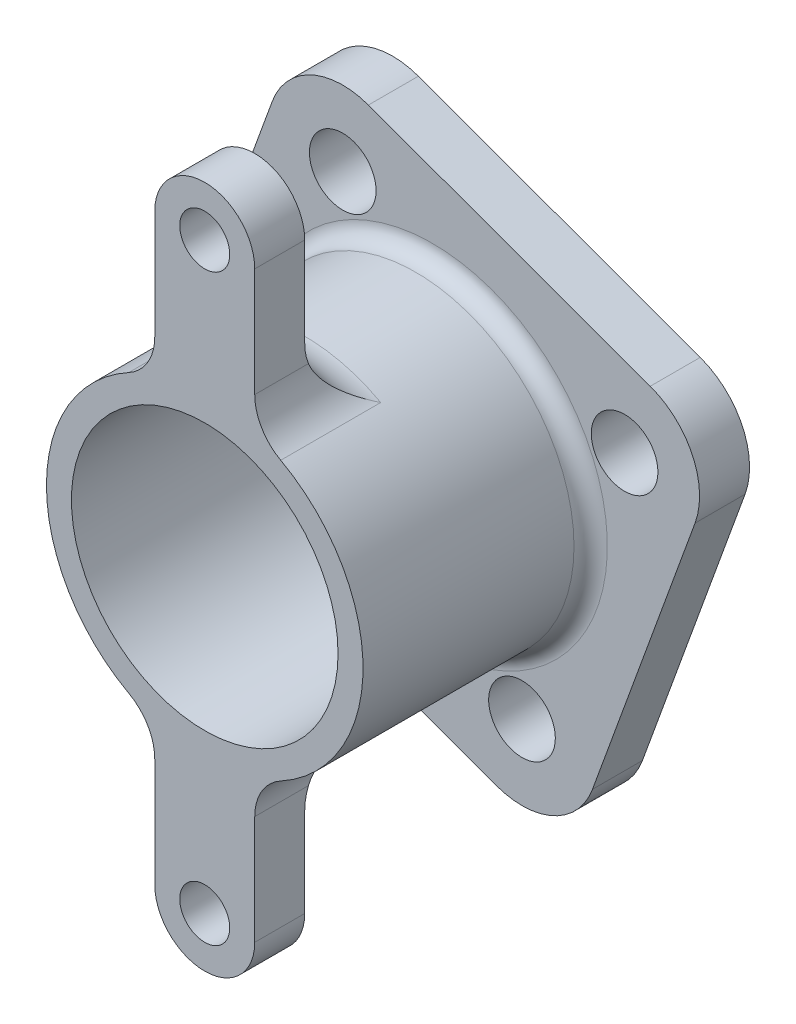
SolidWorks part; units mm, degrees
material "ABS"
ref_plane "Front Plane" through (0, 0, 0) normal (0, 0, 1) x (1, 0, 0)
ref_plane "Top Plane" through (0, 0, 0) normal (0, 1, 0) x (1, 0, 0)
ref_plane "Right Plane" through (0, 0, 0) normal (1, 0, 0) x (0, 0, -1)
sketch "Sketch1" plane through (0, 0, 0) normal (0, 0, 1) x (1, 0, 0)
  line L1 (-20.0745, -9.6077) -> (-3.16, -15.764)
  line L2 (-22.764, -3.84) -> (-16.6077, 13.0745)
  line L3 (-10.84, 15.764) -> (6.0745, 9.6077)
  line L4 (2.6077, -13.0745) -> (8.764, 3.84)
  line L5 (-24.3031, -8.0686) -> (10.3031, 8.0686) construction
  line L6 (-15.0686, 17.3031) -> (1.0686, -17.3031) construction
  line L7 (-18.5354, -5.3791) -> (-1.6209, -11.5354) construction
  line L12 (-18.5354, -5.3791) -> (-12.3791, 11.5354) construction
  line L13 (-12.3791, 11.5354) -> (4.5354, 5.3791) construction
  line L14 (-1.6209, -11.5354) -> (4.5354, 5.3791) construction
  line L15 (-18.5354, -5.3791) -> (4.5354, 5.3791) construction
  line L16 (-12.3791, 11.5354) -> (-1.6209, -11.5354) construction
  arc A4 (6.0745, 9.6077) -> (8.764, 3.84) centre (4.5354, 5.3791) cw
  arc A5 (-3.16, -15.764) -> (2.6077, -13.0745) centre (-1.6209, -11.5354) ccw
  arc A6 (-20.0745, -9.6077) -> (-22.764, -3.84) centre (-18.5354, -5.3791) cw
  arc A7 (-16.6077, 13.0745) -> (-10.84, 15.764) centre (-12.3791, 11.5354) cw
  circle A16 centre (-7, 0) radius 8
  circle A17 centre (-12.3791, 11.5354) radius 2
  circle A18 centre (4.5354, 5.3791) radius 2
  circle A19 centre (-1.6209, -11.5354) radius 2
  circle A20 centre (-18.5354, -5.3791) radius 2
  dimension "D2" = 16
  dimension "D4" = 4.5
  dimension "D6" = 4
  dimension "D1" = 27
  dimension "D3" = 27
  dimension "D5" = 18
extrude "Boss-Extrude1" add sketch "Sketch1" along normal blind 3
sketch "Sketch2" plane through (0, 0, 0) normal (0, 0, 1) x (1, 0, 0)
  circle A1 centre (-7, 0) radius 8
  circle A2 centre (-7, 0) radius 8 construction
  circle A6 centre (-7, 0) radius 9.5
  dimension "D1" = 1.5
extrude "Boss-Extrude2" add sketch "Sketch2" along normal blind 16.66
sketch "Sketch3" plane through (0, 0, 16.66) normal (0, 0, 1) x (1, 0, 0)
  line L0 (-7, 0) -> (17.5448, 0) construction
  line L2 (-10, 17.5) -> (-10, 9.0139)
  line L3 (-4, 17.5) -> (-4, 9.0139)
  line L4 (-7, 0) -> (-7, 6.9852) construction
  line L6 (-4, -17.5) -> (-4, -9.0139)
  line L7 (-10, -17.5) -> (-10, -9.0139)
  circle A4 centre (-7, 0) radius 9.5 construction
  circle A8 centre (-7, 17.5) radius 1.5
  circle A9 centre (-7, 17.5) radius 3
  arc A10 (-10, 9.0139) -> (-4, 9.0139) centre (-7, 0) cw
  arc A11 (-10, -9.0139) -> (-4, -9.0139) centre (-7, 0) ccw
  circle A12 centre (-7, -17.5) radius 3
  circle A13 centre (-7, -17.5) radius 1.5
  dimension "D1" = 3
  dimension "D2" = 6
  dimension "D3" = 35
extrude "Boss-Extrude3" add sketch "Sketch3" against normal blind 3
fillet "Fillet1" radius 3 6 edges at (-7, 9.5, 13.66) (-7, -9.5, 13.66) (-10, -9.0139, 15.16) (-4, -9.0139, 15.16) (-10, 9.0139, 15.16) (-4, 9.0139, 15.16)
fillet "Fillet2" radius 1 1 edges at (-16.5, 0, 3)
